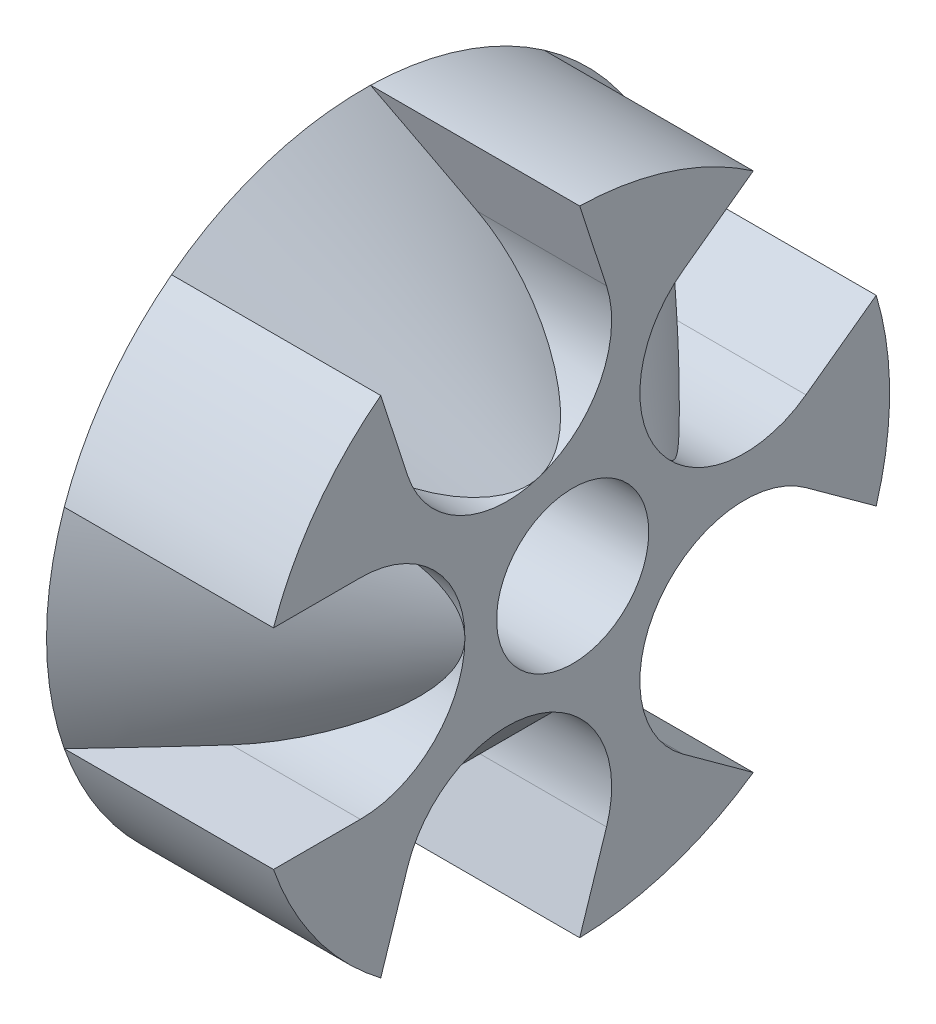
SolidWorks part; units mm, degrees
material "6061 Alloy"
ref_plane "Front Plane" through (0, 0, 0) normal (0, 0, 1) x (1, 0, 0)
ref_plane "Top Plane" through (0, 0, 0) normal (0, 1, 0) x (1, 0, 0)
ref_plane "Right Plane" through (0, 0, 0) normal (1, 0, 0) x (0, 0, -1)
sketch "Sketch1" plane through (0, 0, 0) normal (1, 0, 0) x (0, 0, -1)
  line L0 (55, 0) -> (-55, 0) construction
  circle A0 centre (0, 0) radius 25
  circle A9 centre (0, 0) radius 6
  point P25 (0, 0)
  dimension "D2" = 50
  dimension "D5" = 12
extrude "Boss-Extrude1" add sketch "Sketch1" along normal blind 16.5
sketch "Sketch2" plane through (0, 0, 0) normal (-1, 0, 0) x (0, 0, 1)
  line L0 (55, 0) -> (-55, 0) construction
  line L1 (0, -55) -> (0, 55) construction
  line L2 (0, 9.8706) -> (0, -10.9505) construction
  circle A0 centre (-9.265, 0) radius 1
  circle A1 centre (9.265, 0) radius 1
  dimension "D1" = 9.265
  dimension "D2" = 2
extrude "Cut-Extrude1" [suppressed] cut sketch "Sketch2" against normal blind 25
sketch "Sketch3" plane through (0, 0, 0) normal (0, 1, 0) x (1, 0, 0)
  line L0 (0, -25) -> (16.5, -8.5)
  line L1 (0, -26.7735) -> (0, 26.7735) construction
  line L2 (0, -25) -> (16.5, -25) construction
  line L4 (16.5, -25) -> (16.5, 25) construction
  line L5 (16.5, -8.5) -> (27.2712, -32.48)
  line L6 (27.2712, -32.48) -> (0, -25)
  dimension "D1" = 45
extrude "Cut-Extrude2" [suppressed] cut sketch "Sketch3" against normal mid plane 70 contours L6 L0 L5
sketch "Sketch4" plane through (16.5, 0, 0) normal (1, 0, 0) x (0, 0, -1)
  line L0 (9.075, 0) -> (-9.075, 0) construction
  line L1 (-16.75, 8.25) -> (-27.1788, 8.25)
  line L2 (-27.1788, 8.25) -> (-27.1788, -8.25)
  line L3 (-27.1788, -8.25) -> (-16.75, -8.25)
  line L4 (-25, 0) -> (-25, 11.0415) construction
  line L5 (2.6702, 18.4796) -> (-0.5525, 28.398)
  line L6 (-0.5525, 28.398) -> (-16.2449, 23.2992)
  line L7 (-16.2449, 23.2992) -> (-13.0223, 13.3808)
  line L8 (-7.7254, 23.7764) -> (2.7757, 27.1884) construction
  line L9 (18.4003, 3.171) -> (26.8374, 9.3009)
  line L10 (26.8374, 9.3009) -> (17.1389, 22.6497)
  line L11 (17.1389, 22.6497) -> (8.7018, 16.5198)
  line L12 (20.2254, 14.6946) -> (26.7154, 5.7619) construction
  line L13 (8.7018, -16.5198) -> (17.1389, -22.6497)
  line L14 (17.1389, -22.6497) -> (26.8374, -9.3009)
  line L15 (26.8374, -9.3009) -> (18.4003, -3.171)
  line L16 (20.2254, -14.6946) -> (13.7354, -23.6274) construction
  line L17 (-13.0223, -13.3808) -> (-16.2449, -23.2992)
  line L18 (-16.2449, -23.2992) -> (-0.5525, -28.398)
  line L19 (-0.5525, -28.398) -> (2.6702, -18.4796)
  line L20 (-7.7254, -23.7764) -> (-18.2265, -20.3644) construction
  arc A0 (-16.75, 8.25) -> (-16.75, -8.25) centre (-16.75, 0) cw
  circle A1 centre (0, 0) radius 25 construction
  arc A2 (2.6702, 18.4796) -> (-13.0223, 13.3808) centre (-5.176, 15.9302) cw
  arc A3 (18.4003, 3.171) -> (8.7018, 16.5198) centre (13.551, 9.8454) cw
  arc A4 (8.7018, -16.5198) -> (18.4003, -3.171) centre (13.551, -9.8454) cw
  arc A5 (-13.0223, -13.3808) -> (2.6702, -18.4796) centre (-5.176, -15.9302) cw
  point P41 (0, 0)
  dimension "D1" = 8.25
  dimension "D2" = 8.25
  dimension "D3" = 5
extrude "Cut-Extrude3" cut sketch "Sketch4" against normal blind 30
sketch "Sketch6" plane through (0, 0, 0) normal (0, 1, 0) x (1, 0, 0)
  line L0 (0, -25) -> (16.5, -8.5)
  line L1 (0, -27.4933) -> (0, 27.4933) construction
  line L2 (16.5, -13.0223) -> (16.5, 3.074) construction
  line L3 (16.5, -8.5) -> (0, -8.5)
  line L4 (0, -8.5) -> (0, -25)
  line L5 (27.2308, 0) -> (-10.7308, 0) construction
  dimension "D1" = 45
revolve "Revolve1" add sketch "Sketch6" angle 360 about L5
